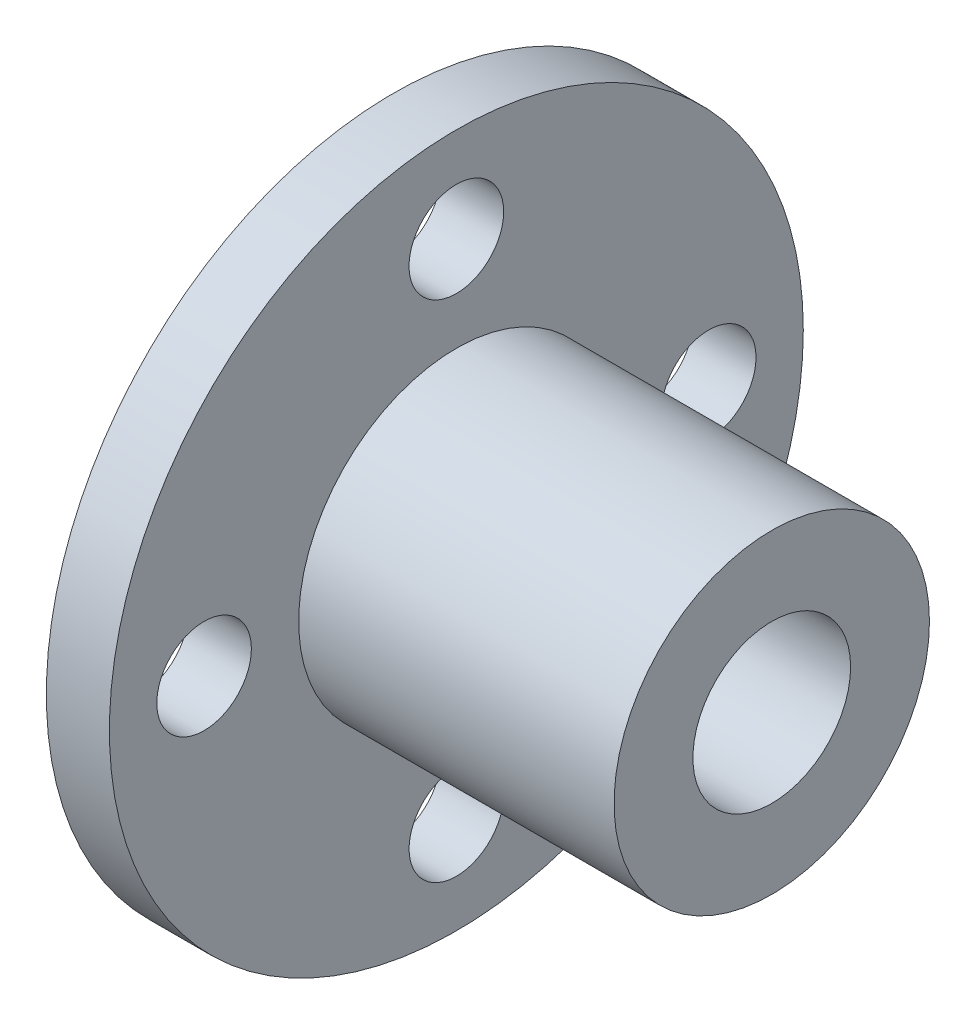
SolidWorks part; units mm, degrees
ref_plane "前视基准面" through (0, 0, 0) normal (0, 0, 1) x (1, 0, 0)
ref_plane "上视基准面" through (0, 0, 0) normal (0, 1, 0) x (1, 0, 0)
ref_plane "右视基准面" through (0, 0, 0) normal (1, 0, 0) x (0, 0, -1)
sketch "草图1" plane through (0, 0, 0) normal (1, 0, 0) x (0, 0, -1)
  circle A0 centre (0, 0) radius 11
  dimension "D1" = 22
extrude "凸台-拉伸1" add sketch "草图1" along normal blind 2
sketch "草图2" plane through (2, 0, 0) normal (1, 0, 0) x (0, 0, -1)
  circle A0 centre (0, 0) radius 5
  circle A1 centre (0, 0) radius 5
  circle A2 centre (0, 0) radius 2.5
  dimension "D1" = 10
  dimension "D2" = 5
extrude "凸台-拉伸2" add sketch "草图2" along normal blind 10 contours A0 A2
sketch "草图3" plane through (2, 0, 0) normal (1, 0, 0) x (0, 0, -1)
  circle A0 centre (0, 0) radius 8 construction
  circle A1 centre (0, 8) radius 1.5
  circle A2 centre (0.001, 0.001) radius 8 construction
  circle A3 centre (8.001, 0.001) radius 1.5
  circle A4 centre (0.002, 0) radius 8 construction
  circle A5 centre (0.002, -8) radius 1.5
  circle A6 centre (0.001, -0.001) radius 8 construction
  circle A7 centre (-7.999, -0.001) radius 1.5
  point P20 (0.001, 0)
  dimension "D1" = 3
  dimension "D2" = 4
extrude "切除-拉伸1" cut sketch "草图3" against normal blind 10
sketch "草图4" plane through (2, 0, 0) normal (1, 0, 0) x (0, 0, -1)
  circle A0 centre (0, 0) radius 2.5
  point P3 (0, 0)
sketch "草图5" plane through (2, 0, 0) normal (1, 0, 0) x (0, 0, -1)
  circle A0 centre (0, 0) radius 2.5 construction
  circle A1 centre (0, 0) radius 2.5
extrude "切除-拉伸2" cut sketch "草图5" against normal through all
